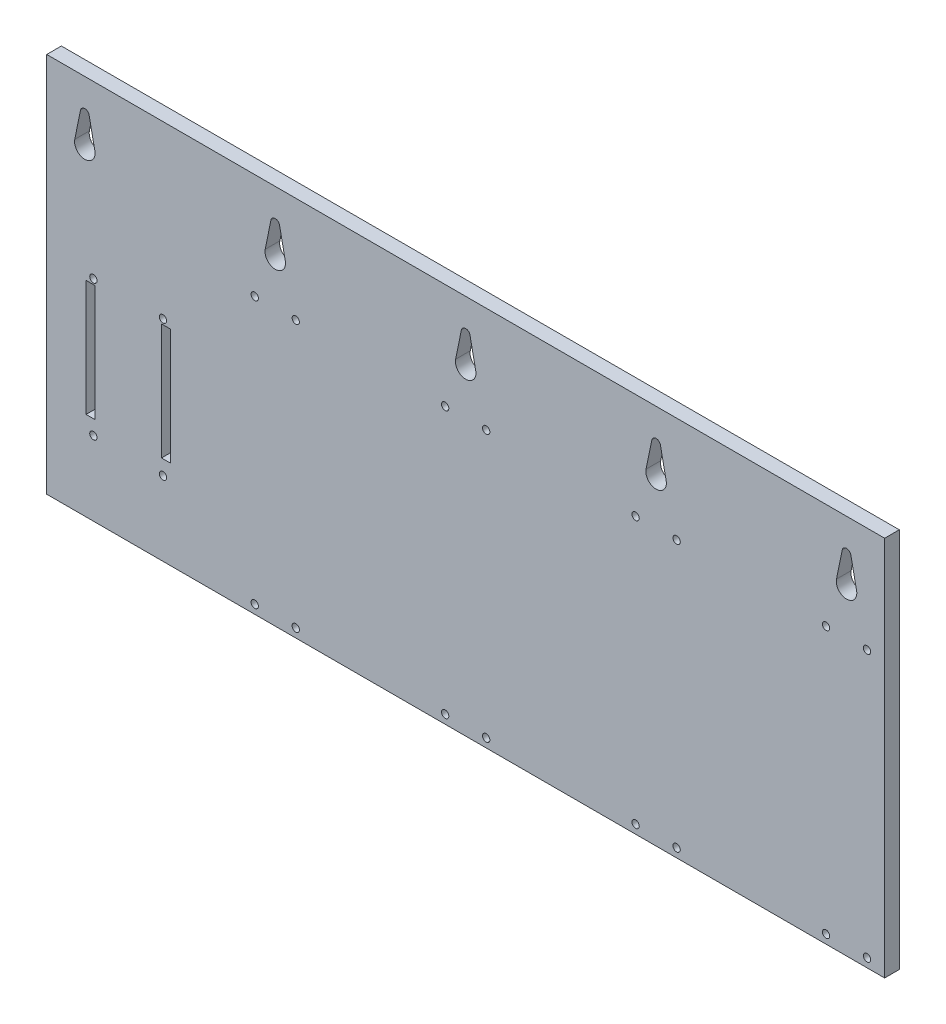
SolidWorks part; units mm, degrees
ref_plane "前基準面" through (0, 0, 0) normal (0, 0, 1) x (1, 0, 0)
ref_plane "上基準面" through (0, 0, 0) normal (0, 1, 0) x (1, 0, 0)
ref_plane "右基準面" through (0, 0, 0) normal (1, 0, 0) x (0, 0, -1)
sketch "草圖1" plane through (0, 0, 0) normal (0, 0, 1) x (1, 0, 0)
  line L0 (-39.5, 45.5) -> (-25.5, 45.5) construction
  line L1 (-110.5, 81.5) -> (110.5, 81.5)
  line L2 (-110.5, 81.5) -> (-110.5, -48.5)
  line L3 (-110.5, -48.5) -> (110.5, -48.5)
  line L4 (110.5, 81.5) -> (110.5, -48.5)
  line L5 (-104.5, 45.5) -> (-90.5, 45.5) construction
  line L6 (-104.5, 45.5) -> (-104.5, -45.5) construction
  line L7 (-104.5, -45.5) -> (-90.5, -45.5) construction
  line L8 (-90.5, 45.5) -> (-90.5, -45.5) construction
  line L9 (-39.5, 45.5) -> (-39.5, -45.5) construction
  line L10 (-25.5, 45.5) -> (-25.5, -45.5) construction
  line L11 (-39.5, -45.5) -> (-25.5, -45.5) construction
  line L12 (25.5, 45.5) -> (39.5, 45.5) construction
  line L13 (25.5, 45.5) -> (25.5, -45.5) construction
  line L14 (39.5, 45.5) -> (39.5, -45.5) construction
  line L15 (25.5, -45.5) -> (39.5, -45.5) construction
  line L16 (90.5, 45.5) -> (104.5, 45.5) construction
  line L17 (90.5, 45.5) -> (90.5, -45.5) construction
  line L18 (104.5, 45.5) -> (104.5, -45.5) construction
  line L19 (90.5, -45.5) -> (104.5, -45.5) construction
  line L20 (-98.9697, 70.8) -> (-100.9293, 61.2)
  line L21 (-96.0303, 70.8) -> (-94.0707, 61.2)
  line L22 (-33.9697, 70.8) -> (-35.9293, 61.2)
  line L23 (-31.0303, 70.8) -> (-29.0707, 61.2)
  line L24 (31.0303, 70.8) -> (29.0707, 61.2)
  line L25 (33.9697, 70.8) -> (35.9293, 61.2)
  line L26 (96.0303, 70.8) -> (94.0707, 61.2)
  line L27 (98.9697, 70.8) -> (100.9293, 61.2)
  arc A0 (-96.0303, 70.8) -> (-98.9697, 70.8) centre (-97.5, 70.5) ccw
  arc A1 (-100.9293, 61.2) -> (-94.0707, 61.2) centre (-97.5, 60.5) ccw
  arc A2 (-35.9293, 61.2) -> (-29.0707, 61.2) centre (-32.5, 60.5) ccw
  arc A3 (-31.0303, 70.8) -> (-33.9697, 70.8) centre (-32.5, 70.5) ccw
  arc A4 (29.0707, 61.2) -> (35.9293, 61.2) centre (32.5, 60.5) ccw
  arc A5 (33.9697, 70.8) -> (31.0303, 70.8) centre (32.5, 70.5) ccw
  arc A6 (94.0707, 61.2) -> (100.9293, 61.2) centre (97.5, 60.5) ccw
  arc A7 (98.9697, 70.8) -> (96.0303, 70.8) centre (97.5, 70.5) ccw
  point P8 (-90.5, 0)
  point P11 (0, 81.5)
  point P26 (-97.5, 45.5)
  dimension "D8" = 1.5
  dimension "D9" = 3.5
  dimension "D11" = 130
  dimension "D1" = 91
  dimension "D2" = 14
  dimension "D3" = 3
  dimension "D4" = 6
  dimension "D6" = 65
  dimension "D7" = 6
  dimension "D10" = 10
  dimension "D12" = 15
  dimension "D5" = 4
extrude "填料-伸長1" add sketch "草圖1" against normal blind 5 contours L4 L1 L2 L3 A7 L27 A6 L26 A5 L25 A4 L24 A3 L23 A2 L22 A1 L20 A0 L21
hole_wizard "M3 螺紋孔1" positions "草圖2" profile "草圖3" tap size "M3" standard "ISO" end condition through all
sketch "草圖2" plane through (0, 0, 0) normal (0, 0, 1) x (1, 0, 0)
  point P0 (-104.5, 45.5)
  point P3 (-90.5, 45.5)
  point P6 (-104.5, -45.5)
  point P9 (-90.5, -45.5)
  point P12 (-39.5, 45.5)
  point P15 (-25.5, 45.5)
  point P18 (-25.5, -45.5)
  point P21 (-39.5, -45.5)
  point P24 (25.5, 45.5)
  point P27 (39.5, 45.5)
  point P30 (39.5, -45.5)
  point P33 (25.5, -45.5)
  point P36 (90.5, 45.5)
  point P39 (104.5, 45.5)
  point P42 (104.5, -45.5)
  point P45 (90.5, -45.5)
sketch "草圖3" plane through (-104.5, 45.5, 0) normal (1, 0, 0) x (0, -1, 0)
  line L0 (0, 0) -> (0, 5)
  line L1 (0, 5) -> (1.25, 5)
  line L2 (1.25, 5) -> (1.25, 0)
  line L5 (1.25, 0) -> (0, 0)
  line L11 (0, -6.35) -> (0, 107.95) construction
  dimension "貫穿螺孔鑽直徑" = 2.5
  dimension "貫穿螺孔鑽深度" = 5
cosmetic thread "鑽孔螺紋1" parameters "D2"=3
cosmetic thread "鑽孔螺紋2" parameters "D2"=3
cosmetic thread "鑽孔螺紋3" parameters "D2"=3
cosmetic thread "鑽孔螺紋4" parameters "D2"=3
cosmetic thread "鑽孔螺紋5" parameters "D2"=3
cosmetic thread "鑽孔螺紋6" parameters "D2"=3
cosmetic thread "鑽孔螺紋7" parameters "D2"=3
cosmetic thread "鑽孔螺紋8" parameters "D2"=3
cosmetic thread "鑽孔螺紋9" parameters "D2"=3
cosmetic thread "鑽孔螺紋10" parameters "D2"=3
cosmetic thread "鑽孔螺紋11" parameters "D2"=3
cosmetic thread "鑽孔螺紋12" parameters "D2"=3
cosmetic thread "鑽孔螺紋13" parameters "D2"=3
cosmetic thread "鑽孔螺紋14" parameters "D2"=3
cosmetic thread "鑽孔螺紋15" parameters "D2"=3
cosmetic thread "鑽孔螺紋16" parameters "D2"=3
sketch "草圖4" plane through (0, 0, 0) normal (0, 0, 1) x (1, 0, 0)
  line L0 (-110.5, 81.5) -> (-110.5, -48.5) construction
  line L1 (-110.5, 81.5) -> (-175.5, 81.5)
  line L2 (-110.5, 81.5) -> (-110.5, -48.5)
  line L3 (-110.5, -48.5) -> (-175.5, -48.5)
  line L12 (-175.5, 81.5) -> (-175.5, -48.5)
  line L13 (-110.5, -48.5) -> (110.5, -48.5) construction
  line L14 (-96.0303, 70.8) -> (-94.0707, 61.2) construction
  line L15 (-130, 43) -> (-65, 43) construction
  line L16 (-130, 43) -> (-130, -43) construction
  line L17 (-130, -43) -> (-65, -43) construction
  line L18 (-65, 43) -> (-65, -43) construction
  line L19 (-98.9697, 70.8) -> (-100.9293, 61.2) construction
  line L20 (-96.0303, 70.8) -> (-94.0707, 61.2)
  line L21 (-98.9697, 70.8) -> (-100.9293, 61.2)
  line L22 (-130, 75.6803) -> (-130, 56.3743) construction
  line L23 (-161.0303, 70.8) -> (-159.0707, 61.2)
  line L24 (-163.9697, 70.8) -> (-165.9293, 61.2)
  arc A0 (-100.9293, 61.2) -> (-94.0707, 61.2) centre (-97.5, 60.5) ccw construction
  arc A1 (-100.9293, 61.2) -> (-94.0707, 61.2) centre (-97.5, 60.5) ccw
  arc A2 (-96.0303, 70.8) -> (-98.9697, 70.8) centre (-97.5, 70.5) ccw construction
  arc A3 (-96.0303, 70.8) -> (-98.9697, 70.8) centre (-97.5, 70.5) ccw
  arc A4 (-163.9697, 70.8) -> (-161.0303, 70.8) centre (-162.5, 70.5) cw
  arc A5 (-159.0707, 61.2) -> (-165.9293, 61.2) centre (-162.5, 60.5) cw
  arc A6 (-31.0303, 70.8) -> (-33.9697, 70.8) centre (-32.5, 70.5) ccw construction
  arc A7 (-31.0303, 70.8) -> (-33.9697, 70.8) centre (-32.5, 70.5) ccw
  point P4 (-135.8189, 0)
  point P17 (-97.5, 43)
  point P21 (-65, 0)
  line B0 (-135.8189, 23.19) -> (-135.8189, -23.19) construction
  line B1 (-135.8189, 23.19) -> (-159.5689, 23.19) construction
  line B2 (-159.5689, 23.19) -> (-159.5689, -23.19) construction
  line B3 (-135.8189, -23.19) -> (-159.5689, -23.19) construction
  line B4 (-133.3189, 21.44) -> (-133.3189, -18.19)
  line B5 (-133.3189, 21.44) -> (-136.3189, 21.44)
  line B6 (-136.3189, 21.44) -> (-136.3189, -18.19)
  line B7 (-133.3189, -18.19) -> (-136.3189, -18.19)
  line B8 (-159.0689, 21.44) -> (-159.0689, -18.19)
  line B9 (-159.0689, 21.44) -> (-162.0689, 21.44)
  line B10 (-162.0689, 21.44) -> (-162.0689, -18.19)
  line B11 (-159.0689, -18.19) -> (-162.0689, -18.19)
  line M51 (-110.5, 81.5) -> (-110.5, -48.5)
  dimension "D1" = 13
  dimension "D2" = 65
  dimension "D3" = 86
  dimension "D4" = 65
  dimension "D5" = 65
  dimension "D6" = 13
sketch_block_instance "圖塊1-1"
sketch_block "圖塊1"
extrude "填料-伸長3" add sketch "草圖4" against normal up to surface (5 mm away) contours L1 L12 L3 B4 B7 B6 B5 B8 B11 B10 B9 M51
hole_wizard "M3 螺紋孔2" positions "草圖5" profile "草圖6" tap size "M3" standard "ISO" end condition through all
sketch "草圖5" plane through (0, 0, 0) normal (0, 0, 1) x (1, 0, 0)
  point P0 (-159.5689, 23.19)
  point P3 (-135.8189, 23.19)
  point P6 (-159.5689, -23.19)
  point P9 (-135.8189, -23.19)
sketch "草圖6" plane through (-159.5689, 23.19, 0) normal (1, 0, 0) x (0, -1, 0)
  line L0 (0, 0) -> (0, 5)
  line L1 (0, 5) -> (1.25, 5)
  line L2 (1.25, 5) -> (1.25, 0)
  line L5 (1.25, 0) -> (0, 0)
  line L11 (0, -6.35) -> (0, 107.95) construction
  dimension "貫穿螺孔鑽直徑" = 2.5
  dimension "貫穿螺孔鑽深度" = 5
cosmetic thread "鑽孔螺紋17" parameters "D2"=3
cosmetic thread "鑽孔螺紋18" parameters "D2"=3
cosmetic thread "鑽孔螺紋19" parameters "D2"=3
cosmetic thread "鑽孔螺紋20" parameters "D2"=3
